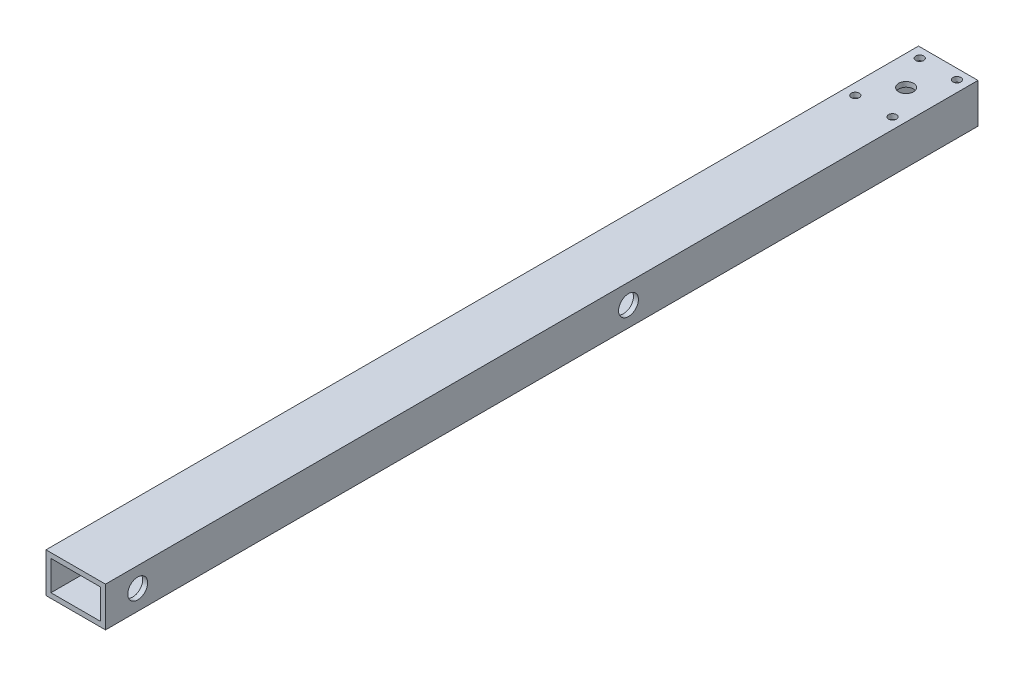
SolidWorks part; units mm, degrees
ref_plane "Front Plane" through (0, 0, 0) normal (0, 0, 1) x (1, 0, 0)
ref_plane "Top Plane" through (0, 0, 0) normal (0, 1, 0) x (1, 0, 0)
ref_plane "Right Plane" through (0, 0, 0) normal (1, 0, 0) x (0, 0, -1)
sketch "Sketch1" plane through (0, 0, 0) normal (0, 0, 1) x (1, 0, 0)
  line L1 (-19.05, 12.7) -> (19.05, 12.7)
  line L2 (-19.05, 12.7) -> (-19.05, -12.7)
  line L3 (-19.05, -12.7) -> (19.05, -12.7)
  line L4 (19.05, 12.7) -> (19.05, -12.7)
  line L5 (-19.05, 12.7) -> (19.05, -12.7) construction
  line L6 (-19.05, -12.7) -> (19.05, 12.7) construction
  line L7 (-15.875, 9.525) -> (15.875, 9.525)
  line L8 (-15.875, 9.525) -> (-15.875, -9.525)
  line L9 (-15.875, -9.525) -> (15.875, -9.525)
  line L10 (15.875, 9.525) -> (15.875, -9.525)
  line L11 (-15.875, 9.525) -> (15.875, -9.525) construction
  line L12 (-15.875, -9.525) -> (15.875, 9.525) construction
  point P0 (0, 0)
  point P6 (0, 0)
  dimension "D1" = 25.4
  dimension "D2" = 38.1
  dimension "D3" = 31.75
  dimension "D4" = 19.05
extrude "Boss-Extrude1" add sketch "Sketch1" along normal blind 558.8
sketch "Sketch2" plane through (0, 12.7, 0) normal (0, 1, 0) x (1, 0, 0)
  line L0 (19.05, 0) -> (-19.05, 0) construction
  circle A0 centre (0, -26.9875) radius 4.7625
  circle A4 centre (11.9062, -47.6097) radius 2.54
  circle A5 centre (-11.9063, -47.6097) radius 2.54
  circle A7 centre (-11.9062, -6.3653) radius 2.54
  circle A8 centre (11.9063, -6.3653) radius 2.54
  point P21 (0, -26.9875)
  dimension "D1" = 9.525
  dimension "D2" = 26.9875
extrude "Cut-Extrude1" cut sketch "Sketch2" against normal up to surface (25.4 mm away) up to face at (0, -12.7, 279.4)
sketch "Sketch3" plane through (-19.05, 0, 0) normal (-1, 0, 0) x (0, 0, 1)
  line L0 (558.8, 12.7) -> (558.8, -12.7) construction
  circle A0 centre (538.1625, 0) radius 3.175
  circle A1 centre (223.8375, 0) radius 3.175
  dimension "D1" = 6.35
  dimension "D3" = 6.35
  dimension "D4" = 334.9625
  dimension "D2" = 20.6375
extrude "Cut-Extrude2" cut sketch "Sketch3" against normal up to surface (3.175 mm away) up to face at (-15.875, 0, 279.4)
sketch "Sketch4" plane through (19.05, 0, 0) normal (1, 0, 0) x (0, 0, -1)
  circle A0 centre (-223.8375, 0) radius 6.35
  circle A1 centre (-223.8375, 0) radius 3.175 construction
  circle A2 centre (-538.1625, 0) radius 6.35
  circle A5 centre (-538.1625, 0) radius 3.175 construction
  dimension "D1" = 12.7
  dimension "D2" = 0
  dimension "D3" = 12.7
  dimension "D4" = 0
extrude "Cut-Extrude3" cut sketch "Sketch4" against normal up to surface (3.175 mm away) up to face at (15.875, 0, 279.4)
